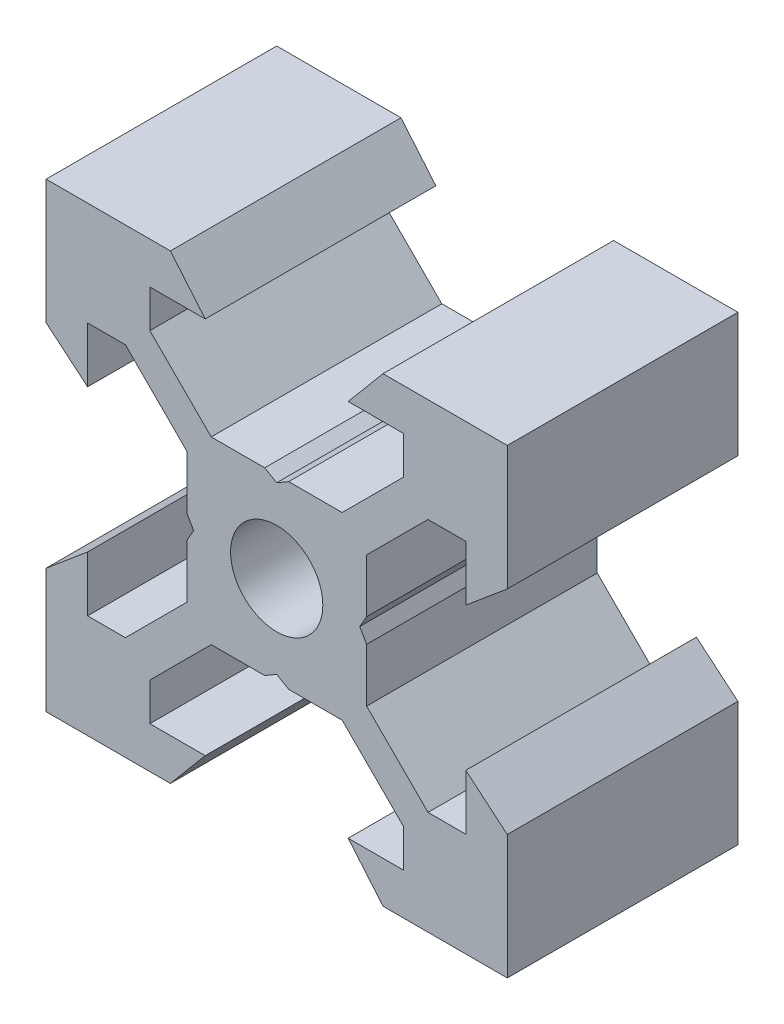
SolidWorks part; units mm, degrees
ref_plane "Front Plane" through (0, 0, 0) normal (0, 0, 1) x (1, 0, 0)
ref_plane "Top Plane" through (0, 0, 0) normal (0, 1, 0) x (1, 0, 0)
ref_plane "Right Plane" through (0, 0, 0) normal (1, 0, 0) x (0, 0, -1)
sketch "Sketch1" plane through (0, 0, 0) normal (0, 0, 1) x (1, 0, 0)
  line L0 (10, 10) -> (4.6104, 10) construction
  line L1 (10, 10) -> (10, 4.6104) construction
  line L2 (10, -10) -> (10, -4.6104) construction
  line L3 (10, -10) -> (4.6104, -10) construction
  line L4 (10, 10) -> (10, 4.6104)
  line L5 (6.5607, 5.5) -> (8.2, 5.5)
  line L6 (5.5, 8.2) -> (5.5, 6.5607)
  line L7 (10, 10) -> (4.6104, 10)
  line L8 (10, 10) -> (10, 4.6104)
  line L9 (6.5607, 5.5) -> (3.9, 2.8393)
  line L10 (5.5, 6.5607) -> (2.8393, 3.9)
  line L11 (10, 4.6104) -> (8.2, 3.1)
  line L12 (4.6104, 10) -> (3.1, 8.2)
  line L13 (8.2, 3.1) -> (8.2, 5.5)
  line L14 (3.1, 8.2) -> (5.5, 8.2)
  line L15 (-6.5607, 5.5) -> (-8.2, 5.5)
  line L16 (6.5607, -5.5) -> (8.2, -5.5)
  line L17 (3.1, -8.2) -> (5.5, -8.2)
  line L18 (8.2, -3.1) -> (8.2, -5.5)
  line L19 (4.6104, -10) -> (3.1, -8.2)
  line L20 (10, -4.6104) -> (8.2, -3.1)
  line L21 (0.5196, -3.9) -> (0, -3.6)
  line L22 (0.5196, 3.9) -> (0, 3.6)
  line L23 (3.6, 0) -> (3.9, -0.5196)
  line L24 (3.9, 0.5196) -> (3.6, 0)
  line L25 (3.9, 0.5196) -> (3.9, 2.8393)
  line L26 (2.8393, 3.9) -> (0.5196, 3.9)
  line L27 (3.9, -2.8393) -> (3.9, -0.5196)
  line L28 (2.8393, -3.9) -> (0.5196, -3.9)
  line L29 (5.5, -6.5607) -> (2.8393, -3.9)
  line L30 (6.5607, -5.5) -> (3.9, -2.8393)
  line L31 (10, -10) -> (10, -4.6104)
  line L32 (10, -10) -> (4.6104, -10)
  line L33 (5.5, -8.2) -> (5.5, -6.5607)
  line L34 (-6.5607, -5.5) -> (-8.2, -5.5)
  line L35 (10, -10) -> (10, -4.6104)
  line L36 (0, 0) -> (0, 8.2) construction
  line L37 (-10, -10) -> (-4.6104, -10) construction
  line L38 (-10, -10) -> (-10, -4.6104) construction
  line L39 (-10, 10) -> (-10, 4.6104) construction
  line L40 (-10, 10) -> (-4.6104, 10) construction
  line L41 (-10, -10) -> (-10, -4.6104)
  line L43 (-5.5, -8.2) -> (-5.5, -6.5607)
  line L44 (-10, -10) -> (-4.6104, -10)
  line L45 (-10, -10) -> (-10, -4.6104)
  line L46 (-6.5607, -5.5) -> (-3.9, -2.8393)
  line L47 (-5.5, -6.5607) -> (-2.8393, -3.9)
  line L48 (-2.8393, -3.9) -> (-0.5196, -3.9)
  line L49 (-3.9, -2.8393) -> (-3.9, -0.5196)
  line L50 (-2.8393, 3.9) -> (-0.5196, 3.9)
  line L51 (-3.9, 0.5196) -> (-3.9, 2.8393)
  line L52 (-3.9, 0.5196) -> (-3.6, 0)
  line L53 (-3.6, 0) -> (-3.9, -0.5196)
  line L54 (-0.5196, 3.9) -> (0, 3.6)
  line L55 (-0.5196, -3.9) -> (0, -3.6)
  line L56 (-10, -4.6104) -> (-8.2, -3.1)
  line L57 (-4.6104, -10) -> (-3.1, -8.2)
  line L58 (-8.2, -3.1) -> (-8.2, -5.5)
  line L59 (-3.1, -8.2) -> (-5.5, -8.2)
  line L60 (-10, -10) -> (10, -10) construction
  line L61 (-10, -10) -> (-10, 10) construction
  line L62 (-3.1, 8.2) -> (-5.5, 8.2)
  line L63 (-8.2, 3.1) -> (-8.2, 5.5)
  line L64 (-4.6104, 10) -> (-3.1, 8.2)
  line L65 (-10, 4.6104) -> (-8.2, 3.1)
  line L66 (-5.5, 6.5607) -> (-2.8393, 3.9)
  line L67 (-6.5607, 5.5) -> (-3.9, 2.8393)
  line L68 (-10, 10) -> (-10, 4.6104)
  line L69 (-10, 10) -> (-4.6104, 10)
  line L70 (-5.5, 8.2) -> (-5.5, 6.5607)
  line L71 (-10, 10) -> (10, 10) construction
  line L72 (-10, 10) -> (-10, 4.6104)
  line L73 (10, -10) -> (10, 10) construction
  line L74 (-10, -10) -> (10, 10) construction
  line L75 (-10, 10) -> (10, -10) construction
  circle A0 centre (0, 0) radius 2
  dimension "D7" = 4
  dimension "D1" = 20
  dimension "D2" = 5.3896
  dimension "D3" = 4.5
  dimension "D4" = 50
  dimension "D5" = 1.8
  dimension "D6" = 1.5104
  dimension "D8" = 5.5
  dimension "D9" = 120
  dimension "D10" = 0.3
  dimension "D11" = 2.3197
  dimension "D12" = 7.8
  dimension "D13" = 7.8
  dimension "D14" = 1.5
  dimension "D15" = 2.6607
extrude "Boss-Extrude1" add sketch "Sketch1" along normal mid plane 10 contours L70 L62 L64 L69 L68 L65 L63 L15 L67 L51 L52 L53 L49 L46 L34 L58 L56 L41 L44 L57 L59 L43 L47 L48 L55 L21 L28 L29 L33 L17 L19 L32 L31 L20 L18 L16 L30 L27 L23 L24 L25 L9 L5 L13 L11 L4 L7 L12 L14 L6 L10
